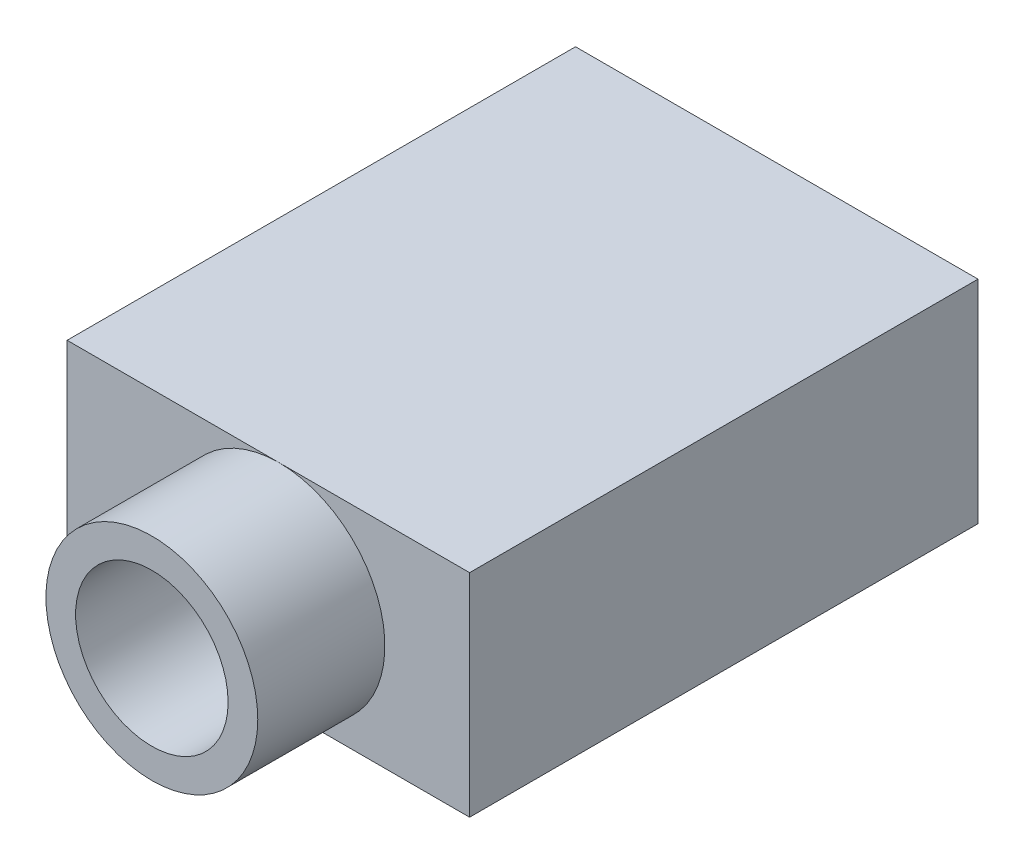
SolidWorks part; units mm, degrees
material "ABS"
ref_plane "Front Plane" through (0, 0, 0) normal (0, 0, 1) x (1, 0, 0)
ref_plane "Top Plane" through (0, 0, 0) normal (0, 1, 0) x (1, 0, 0)
ref_plane "Right Plane" through (0, 0, 0) normal (1, 0, 0) x (0, 0, -1)
sketch "Sketch1" plane through (0, 0, 0) normal (0, 1, 0) x (1, 0, 0)
  line L1 (0, 0) -> (9.5, 0)
  line L2 (0, 0) -> (0, 12)
  line L3 (0, 12) -> (9.5, 12)
  line L4 (9.5, 0) -> (9.5, 12)
  dimension "D1" = 12
  dimension "D2" = 9.5
extrude "Boss-Extrude1" add sketch "Sketch1" along normal blind 5
sketch "Sketch2" plane through (0, 0, 0) normal (0, 0, 1) x (1, 0, 0)
  line L0 (0, 5) -> (0, 0) construction
  line L1 (0, 5) -> (9.5, 5) construction
  circle A0 centre (5, 2.5) radius 2.5
  circle A1 centre (5, 2.5) radius 1.8
  dimension "D1" = 5
  dimension "D4" = 3.6
  dimension "D2" = 5
  dimension "D3" = 2.5
extrude "Boss-Extrude2" add sketch "Sketch2" along normal blind 3
sketch "Sketch3" plane through (0, 0, 0) normal (0, -1, 0) x (1, 0, 0)
  line L0 (9.5, 0) -> (9.5, -12) construction
  line L1 (0, 0) -> (5, 0) construction
  circle A0 centre (5, -3) radius 0.8
  circle A1 centre (5, -9) radius 0.8
  dimension "D5" = 1.6
  dimension "D6" = 1.6
  dimension "D1" = 4.5
  dimension "D2" = 4.5
  dimension "D3" = 6
  dimension "D4" = 3
extrude "Boss-Extrude3" add sketch "Sketch3" along normal blind 1
